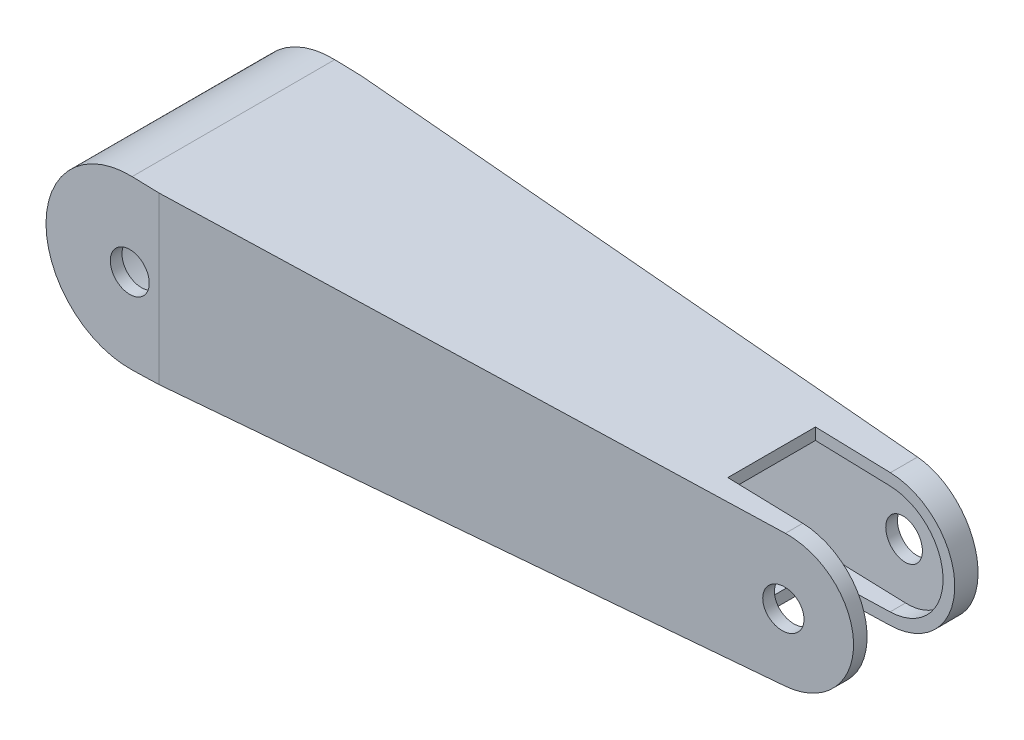
SolidWorks part; units mm, degrees
ref_plane "Plan de face" through (0, 0, 0) normal (0, 0, 1) x (1, 0, 0)
ref_plane "Plan de dessus" through (0, 0, 0) normal (0, 1, 0) x (1, 0, 0)
ref_plane "Plan de droite" through (0, 0, 0) normal (1, 0, 0) x (0, 0, -1)
sketch "Esquisse2" plane through (0, 0, 0) normal (0, 0, 1) x (1, 0, 0)
  line L0 (-160.2273, 0) -> (254.66, 0) construction
  line L1 (-105.5703, 42.9827) -> (211.6745, 33.9863)
  line L2 (-105.5703, -42.9827) -> (211.6745, -33.9863)
  arc A0 (-105.5703, 42.9827) -> (-105.5703, -42.9827) centre (-106.7892, 0) ccw
  arc A1 (211.6745, -33.9863) -> (211.6745, 33.9863) centre (210.7108, 0) ccw
  dimension "D2" = 86
  dimension "D3" = 68
  dimension "D1" = 317.5
extrude "Extrusion1" add sketch "Esquisse2" along normal blind 200
sketch "Esquisse4" plane through (0, 0, 0) normal (0, 1, 0) x (1, 0, 0)
  line L0 (-324.7722, -100) -> (337.3509, -100) construction
  line L1 (-158.7892, -152) -> (-158.7892, -48)
  line L2 (-158.7892, -48) -> (-91.7892, -48)
  line L3 (-91.7892, -48) -> (311.2108, -72)
  line L4 (311.2108, -72) -> (311.2108, -128)
  line L5 (-106.7892, -200) -> (-106.7892, 0) construction
  line L6 (211.6745, -200) -> (-105.5703, -200) construction
  line L7 (-91.7892, -152) -> (311.2108, -128)
  line L8 (-158.7892, -152) -> (-91.7892, -152)
  point P12 (311.2108, -100)
  point P14 (-158.7892, -100)
  dimension "D1" = 52
  dimension "D2" = 28
  dimension "D3" = 67
  dimension "D4" = 52
  dimension "D5" = 470
  dimension "D6" = 100
extrude "Enlèv. mat.-Extru.1" cut sketch "Esquisse4" against normal through all and the other way through all flip side to cut
shell "Coque5" thickness 6
sketch "Esquisse5" plane through (0, 0, 0) normal (0, 1, 0) x (1, 0, 0)
  line L0 (-106.7892, -152) -> (-106.7892, -48) construction
  line L1 (173.2108, -80) -> (273.2108, -80)
  line L2 (173.2108, -80) -> (173.2108, -125)
  line L3 (173.2108, -125) -> (273.2108, -125)
  line L4 (273.2108, -80) -> (273.2108, -125)
  line L5 (-105.5703, -48) -> (-149.7892, -48) construction
  dimension "D1" = 280
  dimension "D2" = 100
  dimension "D3" = 45
  dimension "D4" = 32
extrude "Enlèv. mat.-Extru.2" cut sketch "Esquisse5" against normal through all and the other way through all
sketch "Esquisse6" plane through (0, 0, 152) normal (0, 0, 1) x (1, 0, 0)
  circle A0 centre (210.7108, 0) radius 10
  arc A1 (211.6745, -33.9863) -> (211.6745, 33.9863) centre (210.7108, 0) ccw construction
  dimension "D1" = 20
extrude "Enlèv. mat.-Extru.3" cut sketch "Esquisse6" against normal through all
sketch "Esquisse7" plane through (0, 0, 152) normal (0, 0, 1) x (1, 0, 0)
  circle A0 centre (-106.7892, 0) radius 10
  arc A1 (-105.5703, 42.9827) -> (-105.5703, -42.9827) centre (-106.7892, 0) ccw construction
  dimension "D1" = 20
extrude "Enlèv. mat.-Extru.4" cut sketch "Esquisse7" against normal through all
